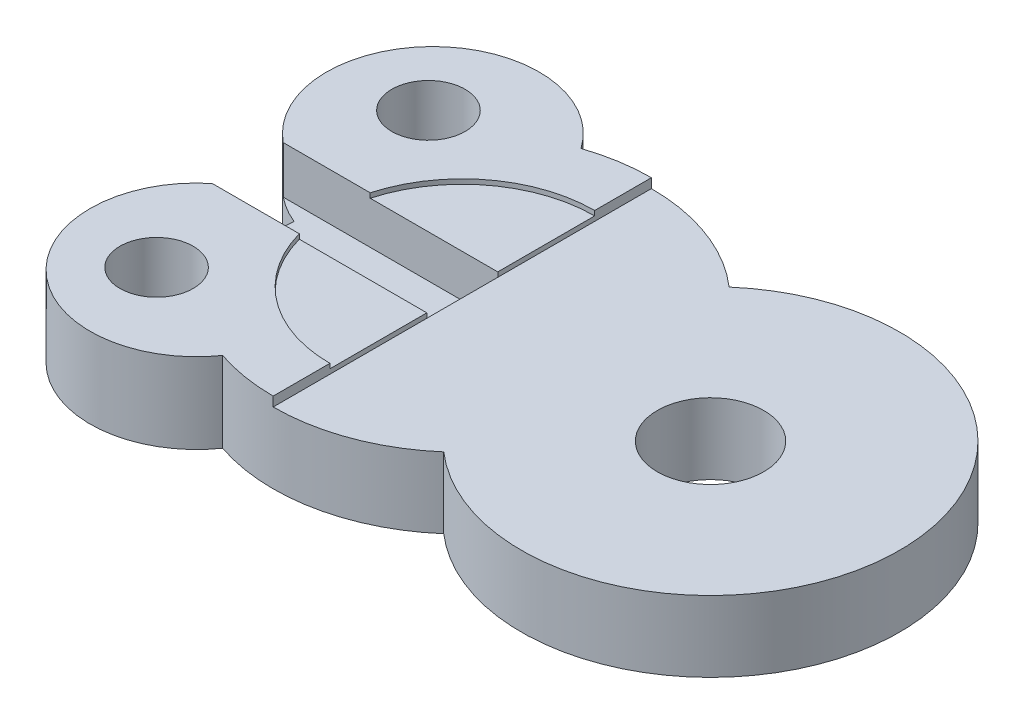
SolidWorks part; units mm, degrees
ref_plane "前视基准面" through (0, 0, 0) normal (0, 0, 1) x (1, 0, 0)
ref_plane "上视基准面" through (0, 0, 0) normal (0, 1, 0) x (1, 0, 0)
ref_plane "右视基准面" through (0, 0, 0) normal (1, 0, 0) x (0, 0, -1)
other "Configuration Table"
sketch "草图1" plane through (0, 0, 0) normal (0, 1, 0) x (1, 0, 0)
  arc A0 (-5.25, -6.0363) -> (-5.25, 6.0363) centre (0, 0) ccw
  circle A1 centre (0, 0) radius 2.25
  arc A2 (-5.25, 6.0363) -> (-13.058, 7.58) centre (-10.5, 0) ccw
  arc A3 (-13.058, 7.58) -> (-18.456, 0.838) centre (-16.745, 5) ccw
  arc A4 (-18.456, -0.838) -> (-13.058, -7.58) centre (-16.745, -5) ccw
  arc A5 (-18.456, 0.838) -> (-18.456, -0.838) centre (-10.5, 0) ccw
  arc A6 (-13.058, -7.58) -> (-5.25, -6.0363) centre (-10.5, 0) ccw
  dimension "D1" = 16
  dimension "D2" = 4.5
  dimension "D4" = 16
  dimension "D7" = 9
  dimension "D8" = 9
  dimension "D3" = 10.5
  dimension "D5" = 5
  dimension "D6" = 5
extrude "凸台-拉伸1" add sketch "草图1" along normal blind 3
sketch "草图5" plane through (0, 3, 0) normal (0, 1, 0) x (1, 0, 0)
  line L1 (-10.5, 8) -> (-10.5, -8)
  arc A14 (-13.058, -7.58) -> (-5.25, -6.0363) centre (-10.5, 0) ccw
  arc A15 (-5.25, -6.0363) -> (-5.25, 6.0363) centre (0, 0) ccw
  arc A16 (-5.25, 6.0363) -> (-13.058, 7.58) centre (-10.5, 0) ccw
  arc A17 (-13.058, 7.58) -> (-18.456, 0.838) centre (-16.745, 5) ccw
  arc A18 (-18.456, 0.838) -> (-18.456, -0.838) centre (-10.5, 0) ccw
  arc A19 (-18.456, -0.838) -> (-13.058, -7.58) centre (-16.745, -5) ccw
  arc A20 (-13.058, -7.58) -> (-10.5, -8) centre (-10.5, 0) ccw
  arc A22 (-10.5, 8) -> (-13.058, 7.58) centre (-10.5, 0) ccw
  arc A23 (-13.058, 7.58) -> (-18.456, 0.838) centre (-16.745, 5) ccw
  arc A24 (-18.456, 0.838) -> (-18.456, -0.838) centre (-10.5, 0) ccw
  arc A25 (-18.456, -0.838) -> (-13.058, -7.58) centre (-16.745, -5) ccw
  dimension "D1" = 0
extrude "凸台-拉伸2" add sketch "草图5" along normal blind 0.4
sketch "草图6" plane through (0, 3.4, 0) normal (0, 1, 0) x (1, 0, 0)
  line L1 (-10.5, 1.5) -> (-23.0225, 1.5)
  line L2 (-10.5, 1.5) -> (-10.5, -1.5)
  line L3 (-10.5, -1.5) -> (-23.0225, -1.5)
  line L4 (-23.0225, 1.5) -> (-23.0225, -1.5)
  line L6 (-10.5, -8) -> (-10.5, 8) construction
  dimension "D1" = 3
  dimension "D2" = 1.5
  dimension "D3" = 0
extrude "切除-拉伸1" cut sketch "草图6" against normal blind 2
sketch "草图7" plane through (0, 3.4, 0) normal (0, 1, 0) x (1, 0, 0)
  line L0 (-10.5, -1.5) -> (-10.5, 1.5) construction
  circle A0 centre (-10.5, 0) radius 5.6
  dimension "D1" = 11.2
extrude "切除-拉伸2" cut sketch "草图7" against normal blind 0.2
sketch "草图9" plane through (0, 3.4, 0) normal (0, 1, 0) x (1, 0, 0)
  line L0 (-10.5, 0) -> (-20.2578, 7.8125) construction
  line L1 (-10.5, 0) -> (-20.2578, -7.8125) construction
  circle A0 centre (-10.5, 0) radius 7.55 construction
  circle A1 centre (-17.6817, 5.75) radius 1.55
  circle A2 centre (-17.6817, -5.75) radius 1.55
  arc A5 (-13.058, 7.58) -> (-19.5734, 1.5) centre (-16.745, 5) ccw construction
  arc A6 (-19.5734, -1.5) -> (-13.058, -7.58) centre (-16.745, -5) ccw construction
  dimension "D1" = 15.1
  dimension "D2" = 3.1
  dimension "D3" = 3.1
  dimension "D4" = 9.2
  dimension "D5" = 9.2
extrude "切除-拉伸3" cut sketch "草图9" against normal through all
